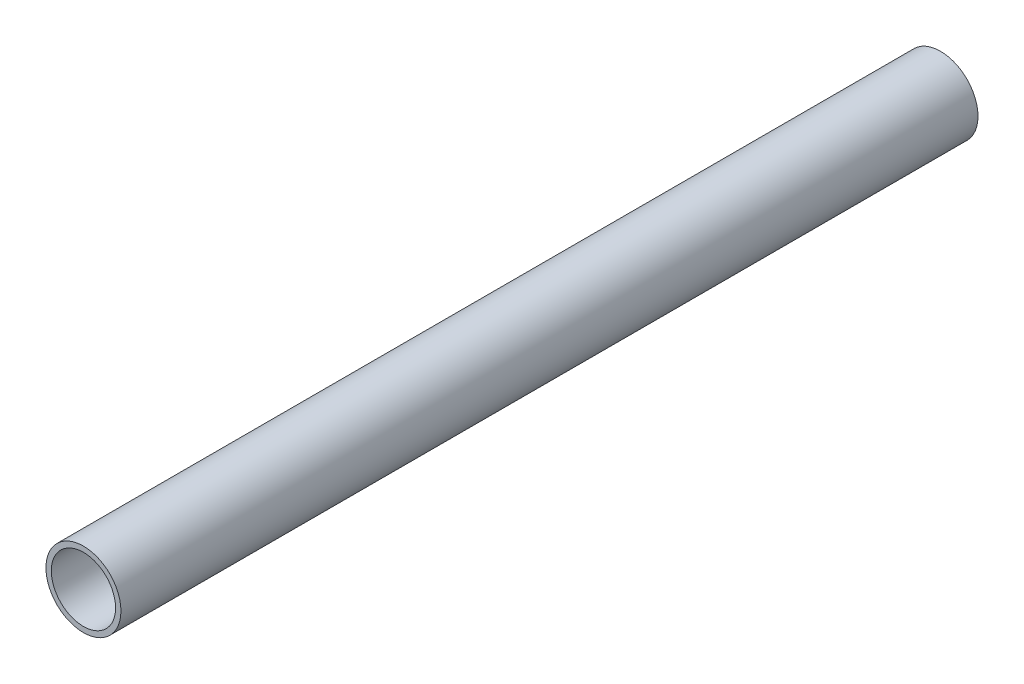
SolidWorks part; units mm, degrees
material "Thornel VCB-20 Carbon Cloth"
ref_plane "Front Plane" through (0, 0, 0) normal (0, 0, 1) x (1, 0, 0)
ref_plane "Top Plane" through (0, 0, 0) normal (0, 1, 0) x (1, 0, 0)
ref_plane "Right Plane" through (0, 0, 0) normal (1, 0, 0) x (0, 0, -1)
sketch "Sketch1" plane through (0, 0, 0) normal (0, 0, 1) x (1, 0, 0)
  circle A0 centre (0, 0) radius 9.525
  circle A1 centre (0, 0) radius 11.1125
  dimension "D1" = 19.05
  dimension "D2" = 22.225
extrude "Boss-Extrude1" add sketch "Sketch1" along normal mid plane 254
